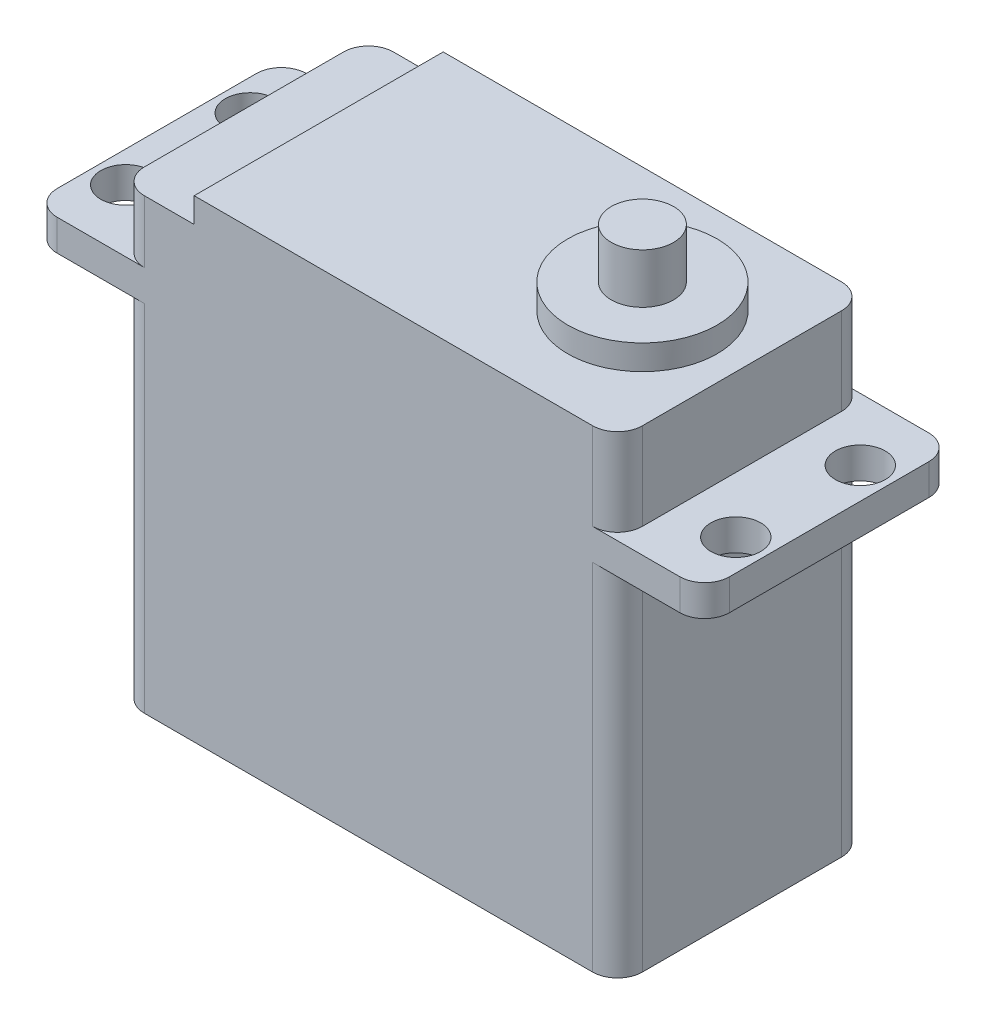
SolidWorks part; units mm, degrees
ref_plane "Plan de face" through (0, 0, 0) normal (0, 0, 1) x (1, 0, 0)
ref_plane "Plan de dessus" through (0, 0, 0) normal (0, 1, 0) x (1, 0, 0)
ref_plane "Plan de droite" through (0, 0, 0) normal (1, 0, 0) x (0, 0, -1)
sketch "Esquisse1" plane through (0, 0, 0) normal (0, 1, 0) x (1, 0, 0)
  line L0 (0, 0) -> (0, 10)
  line L1 (0, 10) -> (40, 10)
  line L2 (40, 10) -> (40, -10)
  line L3 (40, -10) -> (0, -10)
  line L4 (0, -10) -> (0, 0)
  dimension "D1" = 20
  dimension "D2" = 40
  dimension "D3" = 10
extrude "Boss.-Extru.1" add sketch "Esquisse1" along normal blind 36
sketch "Esquisse2" plane through (0, 36, 0) normal (0, 1, 0) x (1, 0, 0)
  line L0 (0, -10) -> (6, -10) construction
  line L1 (0, -10) -> (40, -10) construction
  line L2 (6, -10) -> (6, 10)
  line L3 (40, 10) -> (0, 10) construction
  line L4 (6, 10) -> (40, 10)
  line L5 (40, -10) -> (40, 10) construction
  line L6 (40, 10) -> (40, -10)
  line L7 (40, -10) -> (6, -10)
  dimension "D1" = 6
  dimension "D2" = 34
  dimension "D3" = 20
extrude "Boss.-Extru.2" add sketch "Esquisse2" along normal blind 2
sketch "Esquisse3" plane through (0, 38, 0) normal (0, 1, 0) x (1, 0, 0)
  line L0 (40, 0) -> (0, 0) construction
  line L1 (40, -10) -> (40, 10) construction
  line L2 (0, 0) -> (32, 0) construction
  circle A0 centre (32, 0) radius 6
  point P7 (0, 0)
  dimension "D1" = 32
extrude "Boss.-Extru.3" add sketch "Esquisse3" along normal blind 2
sketch "Esquisse4" plane through (0, 40, 0) normal (0, 1, 0) x (1, 0, 0)
  line L0 (26, 0) -> (38, 0) construction
  circle A0 centre (32, 0) radius 6 construction
  circle A1 centre (32, 0) radius 6 construction
  circle A2 centre (32, 0) radius 2.5
extrude "Boss.-Extru.4" add sketch "Esquisse4" along normal blind 4
sketch "Esquisse5" plane through (0, 0, 0) normal (-1, 0, 0) x (0, 0, 1)
  line L0 (-10, 36) -> (-10, 31) construction
  line L1 (-10, 36) -> (-10, 0) construction
  line L2 (-10, 31) -> (10, 31)
  line L3 (10, 36) -> (10, 0) construction
  line L4 (10, 31) -> (10, 28.5)
  line L5 (10, 28.5) -> (-10, 28.5)
  line L6 (-10, 28.5) -> (-10, 31)
  dimension "D1" = 2.5
extrude "Boss.-Extru.5" add sketch "Esquisse5" along normal blind 7
sketch "Esquisse6" plane through (0, 31, 0) normal (0, 1, 0) x (1, 0, 0)
  line L0 (-7, 0) -> (-7, 5) construction
  line L1 (-7, -10) -> (-7, 10) construction
  line L2 (-7, 5) -> (-4.5, 5) construction
  line L3 (-7, 0) -> (-7, -5) construction
  line L4 (-7, -5) -> (-4.5, -5) construction
  circle A0 centre (-4.5, 5) radius 2
  circle A1 centre (-4.5, -5) radius 2
  dimension "D1" = 5
  dimension "D2" = 2.5
extrude "Enlèv. mat.-Extru.1" cut sketch "Esquisse6" against normal up to next
fillet "Congé1" radius 2 6 edges at (0, 33.5, -10) (0, 33.5, 10) (0, 14.25, 10) (0, 14.25, -10) (-7, 29.75, -10) (-7, 29.75, 10)
sketch "Esquisse7" plane through (40, 0, 0) normal (1, 0, 0) x (0, 0, -1)
  line L0 (-10, 38) -> (-10, 31) construction
  line L2 (-10, 31) -> (10, 31)
  line L4 (10, 31) -> (10, 28.5)
  line L5 (10, 28.5) -> (-10, 28.5)
  line L6 (-10, 28.5) -> (-10, 31)
  dimension "D1" = 2.5
  dimension "D2" = 7
extrude "Boss.-Extru.6" add sketch "Esquisse7" along normal blind 7
sketch "Esquisse8" plane through (0, 31, 0) normal (0, 1, 0) x (1, 0, 0)
  line L0 (47, 0) -> (47, 5) construction
  line L1 (47, 10) -> (47, -10) construction
  line L2 (47, 5) -> (44.5, 5) construction
  line L3 (47, 0) -> (47, -5) construction
  line L4 (47, -5) -> (44.5, -5) construction
  circle A0 centre (44.5, 5) radius 2
  circle A1 centre (44.5, -5) radius 2
  dimension "D1" = 5
  dimension "D2" = 5
  dimension "D3" = 2.5
  dimension "D4" = 2.5
extrude "Enlèv. mat.-Extru.2" cut sketch "Esquisse8" against normal up to next
fillet "Congé2" radius 2 6 edges at (40, 34.5, -10) (47, 29.75, -10) (40, 14.25, -10) (40, 14.25, 10) (40, 34.5, 10) (47, 29.75, 10)
